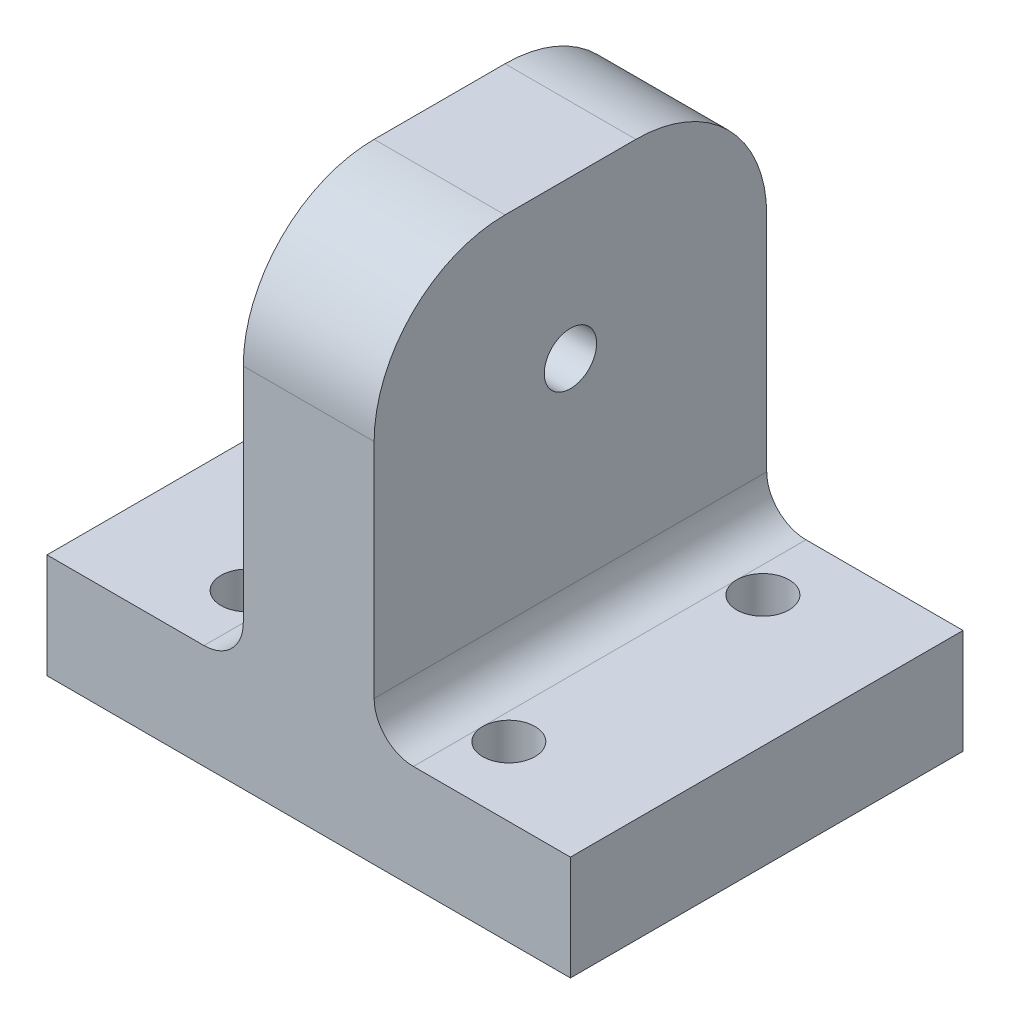
SolidWorks part; units mm, degrees
ref_plane "Front Plane" through (0, 0, 0) normal (0, 0, 1) x (1, 0, 0)
ref_plane "Top Plane" through (0, 0, 0) normal (0, 1, 0) x (1, 0, 0)
ref_plane "Right Plane" through (0, 0, 0) normal (1, 0, 0) x (0, 0, -1)
sketch "Sketch1" plane through (0, 0, 0) normal (0, 1, 0) x (1, 0, 0)
  line L1 (-20, 15) -> (20, 15)
  line L2 (-20, 15) -> (-20, -15)
  line L3 (-20, -15) -> (20, -15)
  line L4 (20, 15) -> (20, -15)
  line L5 (-20, 15) -> (20, -15) construction
  line L6 (-20, -15) -> (20, 15) construction
  point P0 (0, 0)
  dimension "D1" = 40
  dimension "D2" = 30
extrude "Boss-Extrude1" add sketch "Sketch1" along normal blind 8
sketch "Sketch2" plane through (0, 8, 0) normal (0, 1, 0) x (1, 0, 0)
  line L0 (-20, -15) -> (20, -15) construction
  line L1 (-5, 15) -> (5, 15)
  line L2 (-5, 15) -> (-5, -15)
  line L3 (-5, -15) -> (5, -15)
  line L4 (5, 15) -> (5, -15)
  line L5 (-5, 15) -> (5, -15) construction
  line L6 (-5, -15) -> (5, 15) construction
  point P0 (0, 0)
  dimension "D1" = 10
extrude "Boss-Extrude2" add sketch "Sketch2" along normal blind 30
fillet "Fillet2" radius 3 2 edges at (-5, 8, 0) (5, 8, 0)
sketch "Sketch3" plane through (0, 0, 0) normal (0, -1, 0) x (1, 0, 0)
  line L0 (-20, 15) -> (-20, 9.7068) construction
  line L1 (-20, -15) -> (-20, 15) construction
  line L2 (-20, 9.7068) -> (-10, 9.7068) construction
  line L3 (0, 15) -> (0, -15) construction
  line L4 (-20, 15) -> (20, 15) construction
  line L5 (20, -15) -> (-20, -15) construction
  line L6 (-20, 0) -> (20, 0) construction
  line L7 (20, 15) -> (20, -15) construction
  line L8 (-10, -9.7068) -> (10, -9.7068) construction
  circle A0 centre (-10, 9.7068) radius 2
  circle A1 centre (10, 9.7068) radius 2
  circle A2 centre (10, -9.7068) radius 2
  circle A3 centre (-10, -9.7068) radius 2
  dimension "D3" = 4
  dimension "D1" = 5.2932
  dimension "D2" = 10
extrude "Cut-Extrude1" cut sketch "Sketch3" against normal blind 30
sketch "Sketch4" plane through (5, 0, 0) normal (1, 0, 0) x (0, 0, -1)
  line L0 (0, 38) -> (0, 26) construction
  line L1 (-15, 38) -> (15, 38) construction
  circle A0 centre (0, 26) radius 2
  dimension "D2" = 4
  dimension "D1" = 12
extrude "Cut-Extrude2" cut sketch "Sketch4" against normal blind 10
fillet "Fillet3" radius 10 2 edges at (0, 38, 15) (0, 38, -15)
